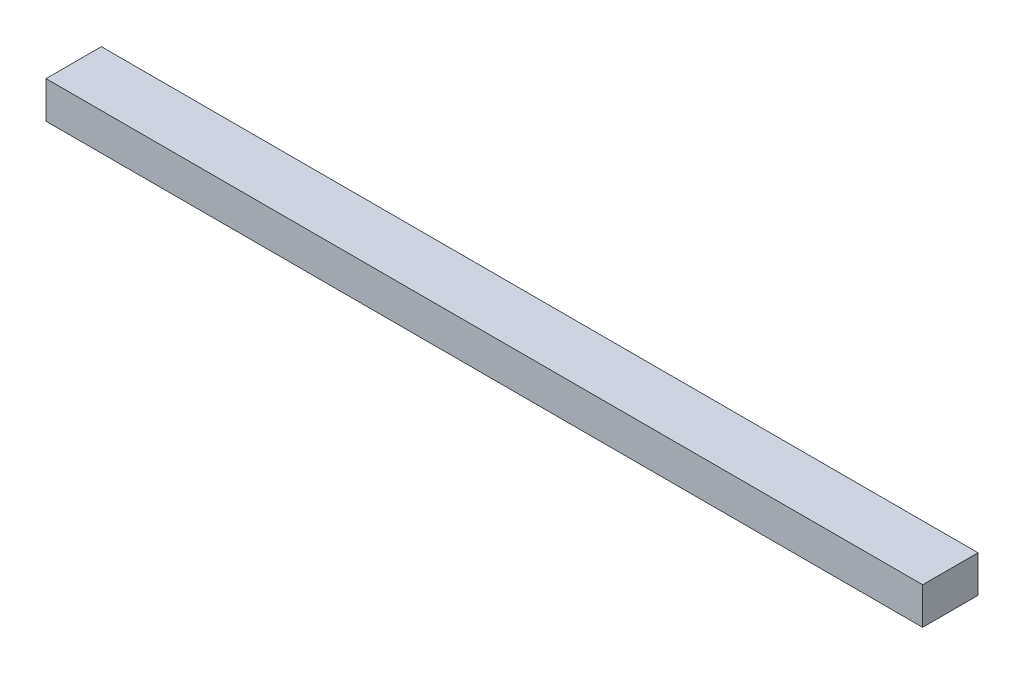
SolidWorks part; units mm, degrees
ref_plane "Front Plane" through (0, 0, 0) normal (0, 0, 1) x (1, 0, 0)
ref_plane "Top Plane" through (0, 0, 0) normal (0, 1, 0) x (1, 0, 0)
ref_plane "Right Plane" through (0, 0, 0) normal (1, 0, 0) x (0, 0, -1)
sketch "Sketch1" plane through (0, 0, 0) normal (0, 1, 0) x (1, 0, 0)
  line L1 (-603.25, -38.1) -> (603.25, -38.1)
  line L2 (-603.25, -38.1) -> (-603.25, 38.1)
  line L3 (-603.25, 38.1) -> (603.25, 38.1)
  line L4 (603.25, -38.1) -> (603.25, 38.1)
  line L5 (-603.25, -38.1) -> (603.25, 38.1) construction
  line L6 (-603.25, 38.1) -> (603.25, -38.1) construction
  point P0 (0, 0)
  dimension "D1" = 1206.5
  dimension "D2" = 76.2
extrude "Boss-Extrude1" add sketch "Sketch1" along normal blind 50.8
